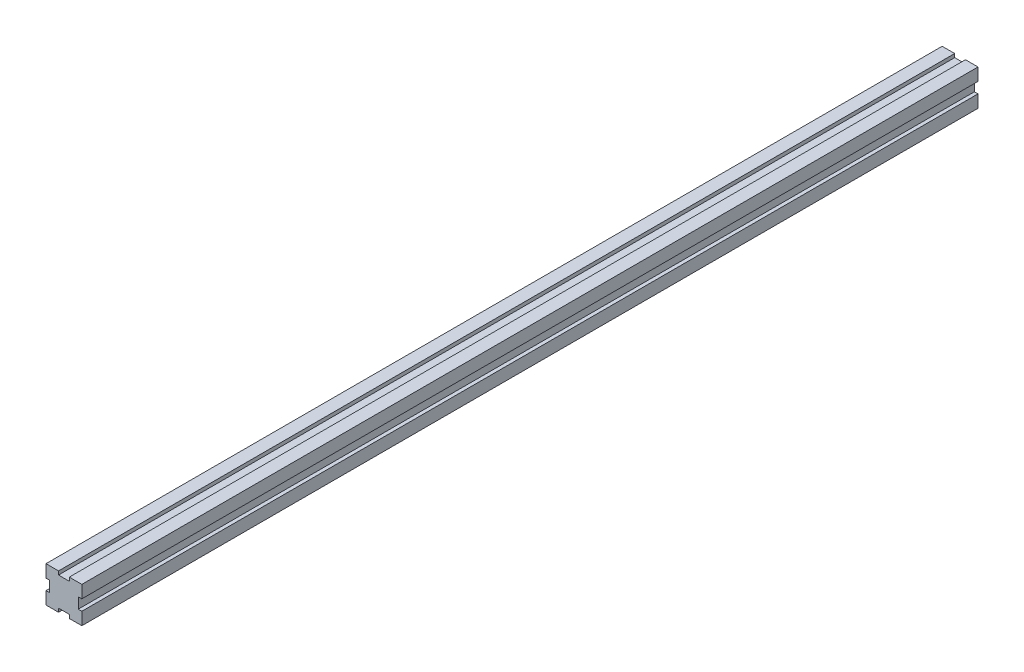
SolidWorks part; units mm, degrees
ref_plane "前视基准面" through (0, 0, 0) normal (0, 0, 1) x (1, 0, 0)
ref_plane "上视基准面" through (0, 0, 0) normal (0, 1, 0) x (1, 0, 0)
ref_plane "右视基准面" through (0, 0, 0) normal (1, 0, 0) x (0, 0, -1)
sketch "草图1" plane through (0, 0, 0) normal (0, 0, 1) x (1, 0, 0)
  line L0 (0, -13) -> (0, -20)
  line L1 (0, 0) -> (7, 0)
  line L2 (0, 0) -> (0, -7)
  line L3 (0, -20) -> (7, -20)
  line L4 (20, 0) -> (20, -7)
  line L5 (20, -7) -> (18, -7)
  line L6 (13, -20) -> (20, -20)
  line L7 (20, -13) -> (18, -13)
  line L8 (18, -7) -> (18, -13)
  line L9 (0, -7) -> (2, -7)
  line L10 (13, 0) -> (20, 0)
  line L11 (0, -13) -> (2, -13)
  line L12 (2, -7) -> (2, -13)
  line L13 (20, -13) -> (20, -20)
  line L14 (7, 0) -> (7, -2)
  line L15 (7, -2) -> (13, -2)
  line L16 (13, 0) -> (13, -2)
  line L17 (0, -7) -> (0, -13) construction
  line L18 (7, -20) -> (7, -18)
  line L19 (7, -18) -> (13, -18)
  line L20 (13, -20) -> (13, -18)
  line L21 (7, 0) -> (13, 0) construction
  line L22 (20, -7) -> (20, -13) construction
  line L23 (13, -20) -> (7, -20) construction
  point P21 (10, 0)
  point P22 (10, -2)
  point P23 (10, -18)
  point P24 (2, -10)
  point P25 (18, -10)
  point P26 (0, -10)
  dimension "D1" = 20
  dimension "D2" = 20
  dimension "D3" = 6
  dimension "D4" = 6
  dimension "D5" = 6
  dimension "D6" = 6
  dimension "D7" = 10
  dimension "D8" = 10
  dimension "D9" = 2
  dimension "D10" = 2
  dimension "D11" = 2
  dimension "D12" = 2
extrude "凸台-拉伸1" add sketch "草图1" along normal blind 500
